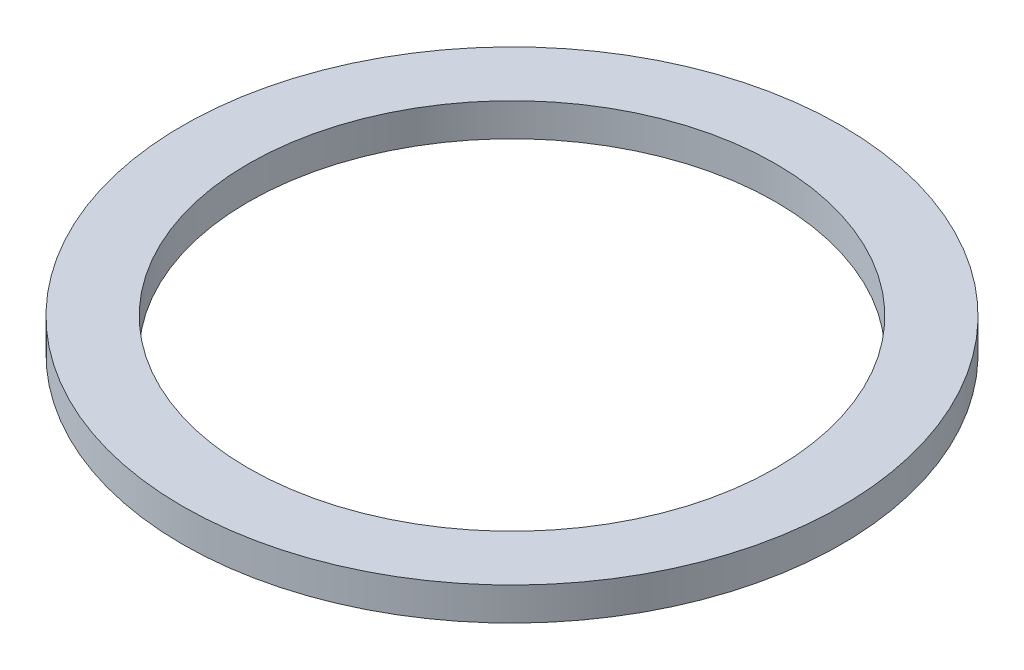
SolidWorks part; units mm, degrees
ref_plane "Front Plane" through (0, 0, 0) normal (0, 0, 1) x (1, 0, 0)
ref_plane "Top Plane" through (0, 0, 0) normal (0, 1, 0) x (1, 0, 0)
ref_plane "Right Plane" through (0, 0, 0) normal (1, 0, 0) x (0, 0, -1)
sketch "Sketch1" plane through (0, 0, 0) normal (0, 1, 0) x (1, 0, 0)
  circle A0 centre (0, 0) radius 40
  circle A1 centre (0, 0) radius 50
  dimension "D1" = 100
  dimension "D2" = 80
extrude "Boss-Extrude1" add sketch "Sketch1" along normal blind 5
